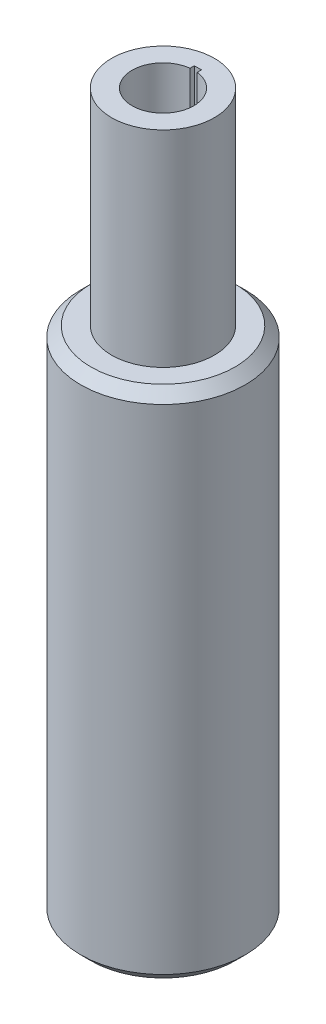
SolidWorks part; units mm, degrees
ref_plane "Alzado" through (0, 0, 0) normal (0, 0, 1) x (1, 0, 0)
ref_plane "Planta" through (0, 0, 0) normal (0, 1, 0) x (1, 0, 0)
ref_plane "Vista lateral" through (0, 0, 0) normal (1, 0, 0) x (0, 0, -1)
sketch "Croquis1" plane through (0, 0, 0) normal (0, 1, 0) x (1, 0, 0)
  circle A0 centre (0, 0) radius 4
  dimension "D1" = 8
extrude "Saliente-Extruir1" add sketch "Croquis1" along normal blind 25
sketch "Croquis2" plane through (0, 25, 0) normal (0, 1, 0) x (1, 0, 0)
  line L2 (-0.175, 1.4898) -> (-0.175, 1.698)
  line L3 (-0.175, 1.698) -> (0.175, 1.698)
  line L4 (0.175, 1.698) -> (0.175, 1.4898)
  circle A0 centre (0, 0) radius 2.5
  arc A1 (-0.175, 1.4898) -> (0.175, 1.4898) centre (0, 0) ccw
  point P9 (0, 1.1494)
  dimension "D1" = 5
  dimension "D2" = 3
  dimension "D3" = 0.2082
  dimension "D4" = 0.2082
extrude "Saliente-Extruir2" add sketch "Croquis2" along normal blind 10
chamfer "Chaflán1" distance 0.5 angle 45 1 edges at (0, 25, 4)
chamfer "Chaflán2" distance 0.5 angle 45 1 edges at (0, 0, 4)
sketch "Croquis4" plane through (0, 0, 0) normal (0, -1, 0) x (1, 0, 0)
  circle A0 centre (0, 0) radius 4
